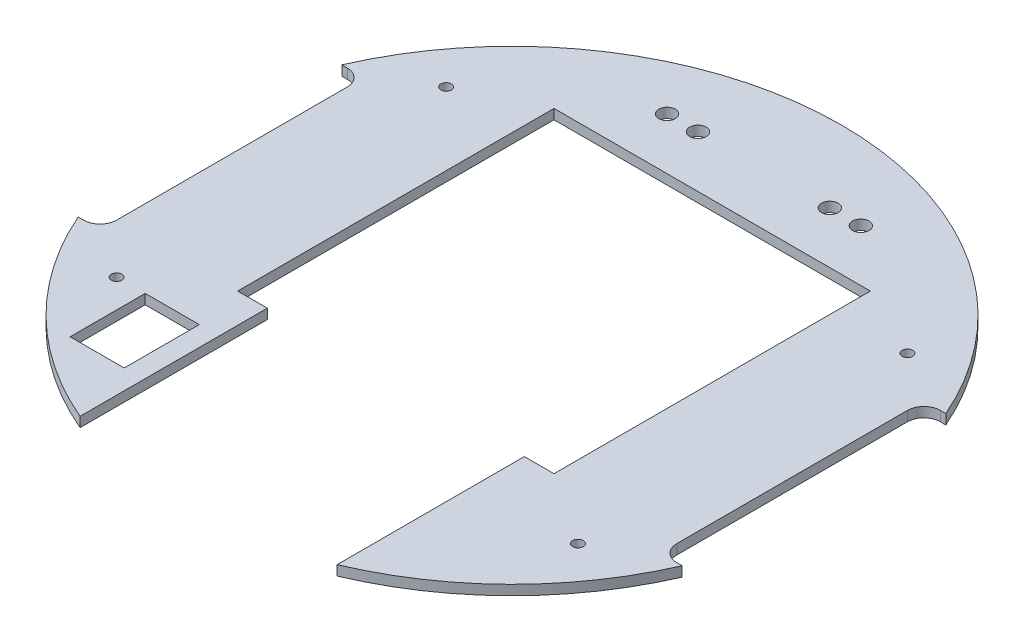
SolidWorks part; units mm, degrees
ref_plane "前基準面" through (0, 0, 0) normal (0, 0, 1) x (1, 0, 0)
ref_plane "上基準面" through (0, 0, 0) normal (0, 1, 0) x (1, 0, 0)
ref_plane "右基準面" through (0, 0, 0) normal (1, 0, 0) x (0, 0, -1)
sketch "草圖1" plane through (0, 0, 0) normal (0, 1, 0) x (1, 0, 0)
  line L0 (-100, 0) -> (100, 0) construction
  line L1 (0, 100) -> (0, -26.56) construction
  line L2 (91.6515, -40) -> (90, -40)
  line L4 (-39, -35.1836) -> (-39, -97.3943)
  line L5 (-39, -97.3943) -> (39, -97.3943)
  line L6 (39, -35.1836) -> (39, -97.3943)
  line L7 (-39, -35.1836) -> (39, -97.3943) construction
  line L8 (-39, -97.3943) -> (39, -35.1836) construction
  line L9 (-91.6515, 40) -> (-90, 40)
  line L10 (-61.4048, -49.9009) -> (-45.0048, -49.9009)
  line L11 (-61.4048, -49.9009) -> (-61.4048, -72.7009)
  line L12 (-61.4048, -72.7009) -> (-45.0048, -72.7009)
  line L13 (-45.0048, -49.9009) -> (-45.0048, -72.7009)
  line L15 (-91.6515, -40) -> (-90, -40)
  line L16 (-85, 35) -> (-85, -35)
  line L17 (-104.267, 0) -> (-85, -40) construction
  line L18 (-104.267, 0) -> (-85, 40) construction
  line L19 (85, 35) -> (85, -35)
  line L20 (91.6515, 40) -> (90, 40)
  line L22 (38.9043, -35.26) -> (48, -35.26)
  line L23 (-48, 60.74) -> (48, 60.74)
  line L24 (-48, 60.74) -> (-48, -35.26)
  line L25 (-48, -35.26) -> (-38.9043, -35.26)
  line L26 (48, 60.74) -> (48, -35.26)
  line L27 (-48, 60.74) -> (48, -35.26) construction
  line L28 (-48, -35.26) -> (48, 60.74) construction
  line L29 (0, -35.1836) -> (0, -100) construction
  circle A0 centre (0, 0) radius 100
  circle A2 centre (-70, -50) radius 1.6
  circle A3 centre (70, -50) radius 1.6
  circle A4 centre (70, 50) radius 1.6
  circle A5 centre (-70, 50) radius 1.6
  circle A6 centre (-29.4, 76.4433) radius 2.5
  circle A7 centre (-20, 76.4433) radius 2.5
  circle A8 centre (20, 76.4433) radius 2.5
  circle A9 centre (29.4, 76.4433) radius 2.5
  arc A10 (-85, 35) -> (-90, 40) centre (-90, 35) ccw
  arc A11 (-85, -35) -> (-90, -40) centre (-90, -35) cw
  arc A12 (85, -35) -> (90, -40) centre (90, -35) ccw
  arc A13 (85, 35) -> (90, 40) centre (90, 35) cw
  point P5 (0, 12.74)
  point P17 (0, -66.2889)
  point P34 (-104.267, 0)
  point P59 (0, 18.7971)
  dimension "D1" = 200
  dimension "D3" = 96
  dimension "D6" = 3.2
  dimension "D12" = 5
  dimension "D14" = 5
  dimension "D17" = 5
  dimension "D15" = 5
  dimension "D2" = 96
  dimension "D4" = 50
  dimension "D5" = 70
  dimension "D8" = 78
  dimension "D9" = 16.4
  dimension "D10" = 22.8
  dimension "D11" = 29.4
  dimension "D13" = 20
  dimension "D16" = 15
  dimension "D18" = 12.74
extrude "填料-伸長1" add sketch "草圖1" along normal blind 3
sketch "草圖3" plane through (0, 0, 0) normal (0, 1, 0) x (1, 0, 0)
